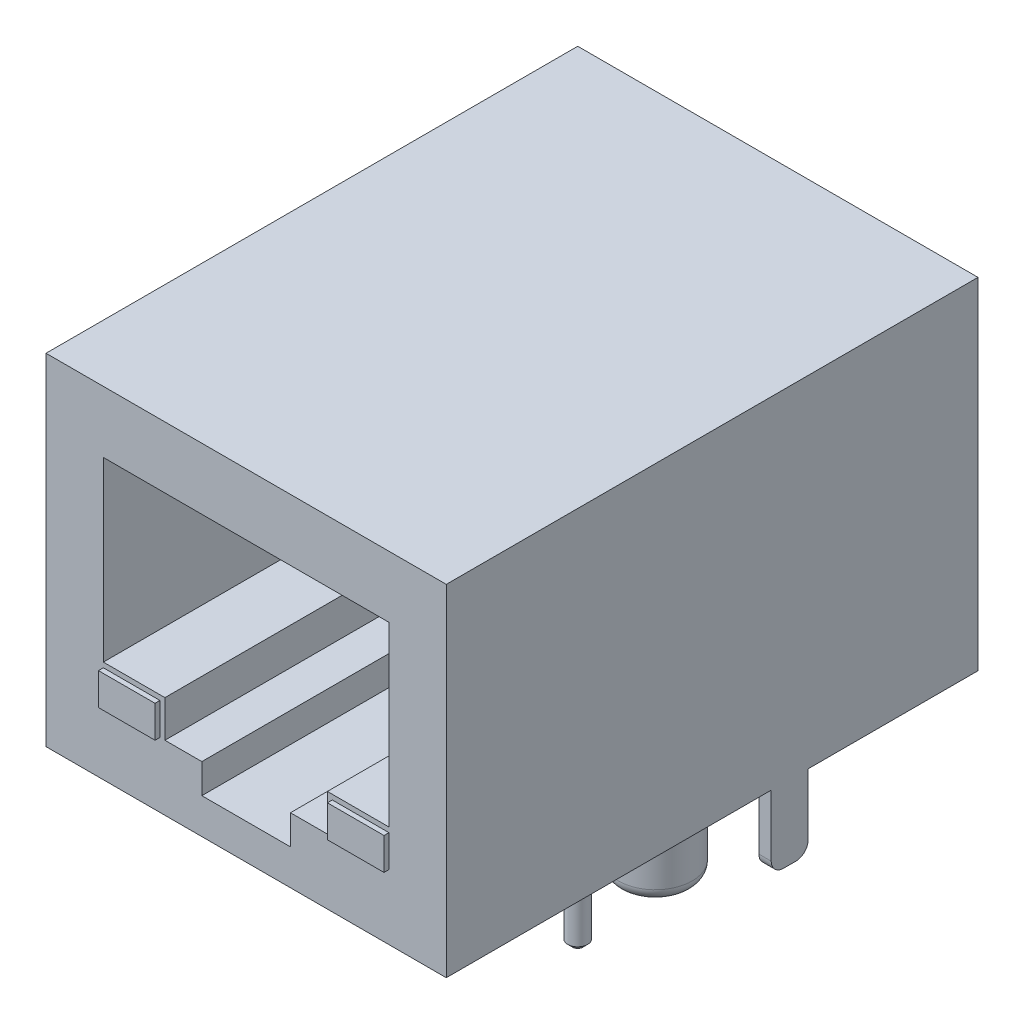
SolidWorks part; units mm, degrees
ref_plane "Спереди" through (0, 0, 0) normal (0, 0, 1) x (1, 0, 0)
ref_plane "Сверху" through (0, 0, 0) normal (0, 1, 0) x (1, 0, 0)
ref_plane "Справа" through (0, 0, 0) normal (1, 0, 0) x (0, 0, -1)
sketch "Эскиз1" plane through (0, 0, 0) normal (0, 1, 0) x (1, 0, 0)
  line L1 (8.13, -10.8) -> (-8.13, -10.8)
  line L2 (8.13, -10.8) -> (8.13, 10.8)
  line L3 (8.13, 10.8) -> (-8.13, 10.8)
  line L4 (-8.13, -10.8) -> (-8.13, 10.8)
  line L5 (8.13, -10.8) -> (-8.13, 10.8) construction
  line L6 (8.13, 10.8) -> (-8.13, -10.8) construction
  point P0 (0, 0)
  dimension "D1" = 21.6
  dimension "D2" = 16.26
extrude "Бобышка-Вытянуть1" add sketch "Эскиз1" along normal blind 13.84
sketch "Эскиз2" plane through (0, 0, 0) normal (0, 1, 0) x (1, 0, 0)
  line L0 (-8.13, -10.8) -> (8.13, -10.8) construction
  circle A0 centre (5.72, 0.1) radius 1.5
  circle A1 centre (-5.72, 0.1) radius 1.5
  dimension "D1" = 5.72
  dimension "D5" = 3
  dimension "D6" = 3
  dimension "D2" = 5.72
  dimension "D3" = 10.9
  dimension "D4" = 10.9
extrude "Бобышка-Вытянуть2" add sketch "Эскиз2" against normal blind 3
fillet "Скругление1" radius 0.5 2 edges at (-5.72, -3, 1.4) (5.72, -3, 1.4)
sketch "Эскиз3" plane through (0, 0, 0) normal (0, 1, 0) x (1, 0, 0)
  line L0 (-8.13, 10.8) -> (-8.13, -10.8) construction
  line L1 (-8.13, 3.9) -> (-7.63, 3.9)
  line L2 (-8.13, 3.9) -> (-8.13, 2.4)
  line L3 (-8.13, 2.4) -> (-7.63, 2.4)
  line L4 (-7.63, 3.9) -> (-7.63, 2.4)
  line L5 (-8.13, 3.9) -> (-7.63, 2.4) construction
  line L6 (-8.13, 2.4) -> (-7.63, 3.9) construction
  line L7 (7.63, 3.9) -> (8.13, 3.9)
  line L8 (7.63, 3.9) -> (7.63, 2.4)
  line L9 (7.63, 2.4) -> (8.13, 2.4)
  line L10 (8.13, 3.9) -> (8.13, 2.4)
  line L11 (7.63, 3.9) -> (8.13, 2.4) construction
  line L12 (7.63, 2.4) -> (8.13, 3.9) construction
  line L13 (-8.13, -10.8) -> (8.13, -10.8) construction
  line L14 (8.13, -10.8) -> (8.13, 10.8) construction
  point P0 (-7.88, 3.15)
  point P5 (7.88, 3.15)
  dimension "D1" = 0
  dimension "D2" = 1.5
  dimension "D3" = 0.5
  dimension "D4" = 13.95
  dimension "D5" = 13.95
  dimension "D6" = 0
  dimension "D7" = 1.5
  dimension "D8" = 0.5
extrude "Бобышка-Вытянуть3" add sketch "Эскиз3" against normal blind 3
fillet "Скругление2" radius 0.5 4 edges at (7.88, -3, -3.9) (7.88, -3, -2.4) (-7.88, -3, -2.4) (-7.88, -3, -3.9)
sketch "Эскиз4" plane through (0, 0, 0) normal (0, 1, 0) x (1, 0, 0)
  line L0 (-8.13, -10.8) -> (8.13, -10.8) construction
  circle A0 centre (-6.63, -3.96) radius 0.4
  circle A1 centre (-4.09, -3.96) radius 0.4
  circle A2 centre (4.09, -3.96) radius 0.4
  circle A3 centre (6.63, -3.96) radius 0.4
  dimension "D1" = 4.09
  dimension "D5" = 0.8
  dimension "D6" = 0.8
  dimension "D11" = 0.8
  dimension "D12" = 0.8
  dimension "D2" = 6.84
  dimension "D3" = 6.84
  dimension "D4" = 6.63
  dimension "D7" = 6.84
  dimension "D8" = 6.84
  dimension "D9" = 4.09
  dimension "D10" = 6.63
extrude "Бобышка-Вытянуть4" add sketch "Эскиз4" against normal blind 3
sketch "Эскиз5" plane through (0, 0, 0) normal (0, 1, 0) x (1, 0, 0)
  line L0 (-8.13, -10.8) -> (8.13, -10.8) construction
  circle A0 centre (-4.45, 6.46) radius 0.35
  circle A1 centre (-3.18, 9) radius 0.35
  dimension "D1" = 19.8
  dimension "D2" = 0.7
  dimension "D3" = 0.7
  dimension "D4" = 4.45
  dimension "D5" = 2.54
  dimension "D6" = 1.27
extrude "Бобышка-Вытянуть5" add sketch "Эскиз5" against normal blind 3
pattern_linear "Линейный массив1" count 4 spacing 2.54 along (1, 0, 0) of "Бобышка-Вытянуть5"
chamfer "Фаска1" distance 0.2 angle 45 12 edges at (3.17, -3, -6.11) (4.44, -3, -8.65) (1.9, -3, -8.65) (0.63, -3, -6.11) (-1.91, -3, -6.11) (-0.64, -3, -8.65) (-4.45, -3, -6.11) (-3.18, -3, -8.65) (-6.63, -3, 4.36) (-4.09, -3, 4.36) (4.09, -3, 4.36) (6.63, -3, 4.36)
sketch "Эскиз6" plane through (0, 0, 10.8) normal (0, 0, 1) x (1, 0, 0)
  line L0 (-5.8, 11.34) -> (5.8, 11.34)
  line L1 (5.8, 11.34) -> (5.8, 4.14)
  line L2 (5.8, 4.14) -> (3.3, 4.14)
  line L3 (3.3, 4.14) -> (3.3, 2.64)
  line L4 (3.3, 2.64) -> (1.8, 2.64)
  line L5 (1.8, 2.64) -> (1.8, 1.44)
  line L6 (1.8, 1.44) -> (-1.8, 1.44)
  line L7 (-1.8, 1.44) -> (-1.8, 2.64)
  line L8 (-1.8, 2.64) -> (-3.3, 2.64)
  line L9 (-3.3, 2.64) -> (-3.3, 4.14)
  line L10 (-3.3, 4.14) -> (-5.8, 4.14)
  line L11 (-5.8, 4.14) -> (-5.8, 11.34)
  line L12 (-8.13, 13.84) -> (-8.13, 0) construction
  line L13 (-8.13, 13.84) -> (8.13, 13.84) construction
  dimension "D1" = 11.6
  dimension "D2" = 5.8
  dimension "D3" = 2.33
  dimension "D4" = 2.5
  dimension "D5" = 7.2
  dimension "D6" = 6.6
  dimension "D7" = 3.3
  dimension "D8" = 7.2
  dimension "D9" = 3.6
  dimension "D10" = 1.8
  dimension "D11" = 1.5
  dimension "D12" = 1.5
  dimension "D13" = 1.2
extrude "Вырез-Вытянуть1" cut sketch "Эскиз6" against normal blind 13
sketch "Эскиз7" plane through (0, 0, 10.8) normal (0, 0, 1) x (1, 0, 0)
  line L0 (-5.8, 4.14) -> (-3.3, 4.14) construction
  line L1 (-5.8, 3.94) -> (-3.5, 3.94)
  line L2 (-5.8, 3.94) -> (-5.8, 2.64)
  line L3 (-5.8, 2.64) -> (-3.5, 2.64)
  line L4 (-3.5, 3.94) -> (-3.5, 2.64)
  line L5 (-3.3, 4.14) -> (-3.3, 2.64) construction
  line L6 (-5.8, 11.34) -> (-5.8, 4.14) construction
  line L7 (-3.3, 2.64) -> (-1.8, 2.64) construction
  dimension "D1" = 0.2
  dimension "D2" = 0.2
  dimension "D3" = 0
  dimension "D4" = 0
extrude "Бобышка-Вытянуть6" add sketch "Эскиз7" along normal blind 0.2
sketch "Эскиз8" plane through (0, 0, 10.8) normal (0, 0, 1) x (1, 0, 0)
  line L0 (3.3, 4.14) -> (5.8, 4.14) construction
  line L1 (3.5, 3.94) -> (5.8, 3.94)
  line L2 (3.5, 3.94) -> (3.5, 2.64)
  line L3 (3.5, 2.64) -> (5.8, 2.64)
  line L4 (5.8, 3.94) -> (5.8, 2.64)
  line L5 (3.3, 2.64) -> (3.3, 4.14) construction
  line L6 (1.8, 2.64) -> (3.3, 2.64) construction
  line L7 (5.8, 4.14) -> (5.8, 11.34) construction
  dimension "D1" = 0.2
  dimension "D2" = 0.2
  dimension "D3" = 0
  dimension "D4" = 0
extrude "Бобышка-Вытянуть7" add sketch "Эскиз8" along normal blind 0.2
